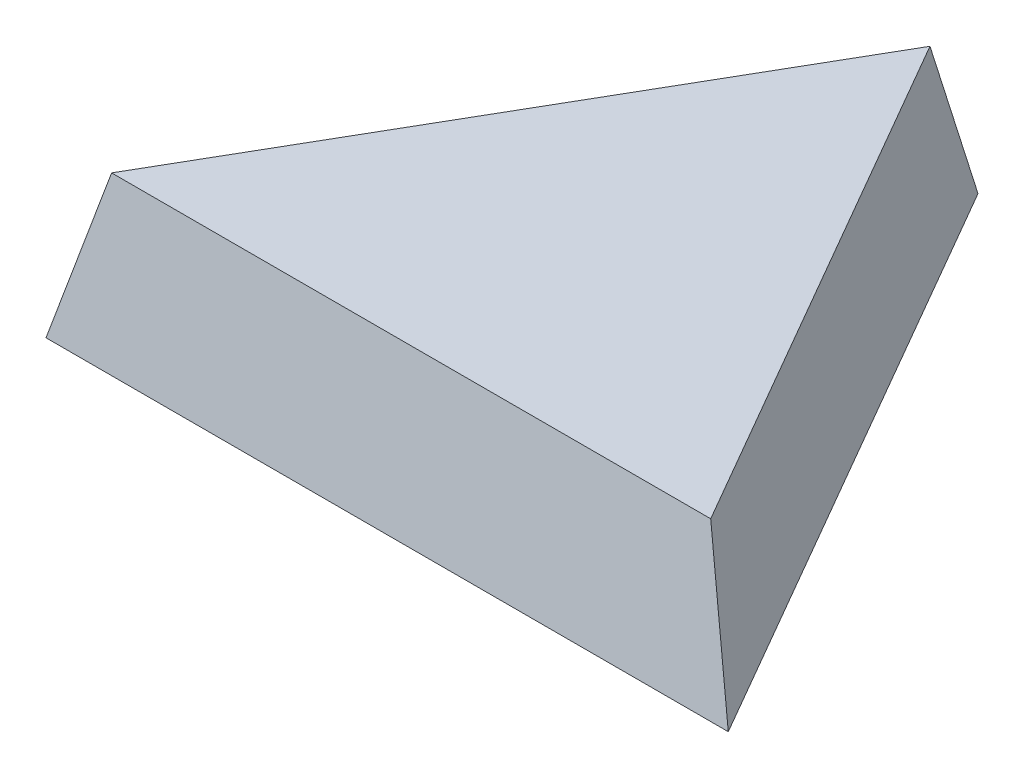
SolidWorks part; units mm, degrees
ref_plane "Front Plane" through (0, 0, 0) normal (0, 0, 1) x (1, 0, 0)
ref_plane "Top Plane" through (0, 0, 0) normal (0, 1, 0) x (1, 0, 0)
ref_plane "Right Plane" through (0, 0, 0) normal (1, 0, 0) x (0, 0, -1)
sketch "Sketch1" plane through (0, 0, 0) normal (0, 1, 0) x (1, 0, 0)
  line L1 (3.4337, -0.8559) -> (-1.0663, 6.9384)
  line L2 (-1.0663, 6.9384) -> (-5.5663, -0.8559)
  line L3 (-5.5663, -0.8559) -> (3.4337, -0.8559)
extrude "Boss-Extrude1" add sketch "Sketch1" along normal blind 2 draft 9
